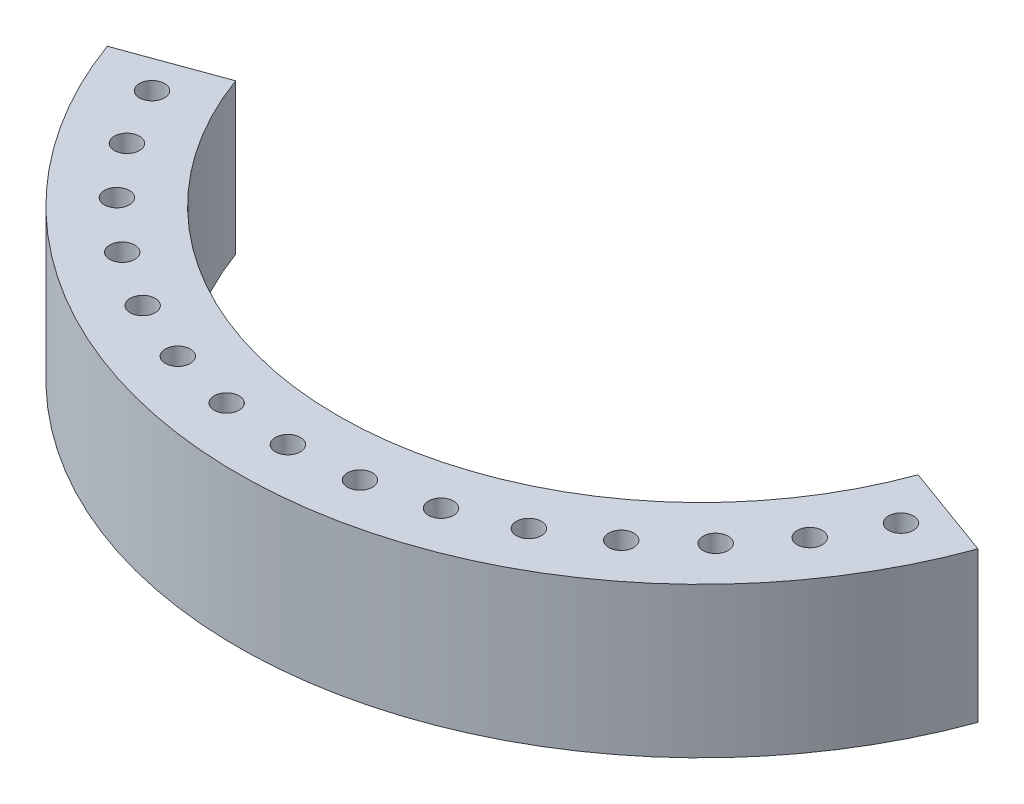
SolidWorks part; units mm, degrees
ref_plane "Front" through (0, 0, 0) normal (0, 0, 1) x (1, 0, 0)
ref_plane "Top" through (0, 0, 0) normal (0, 1, 0) x (1, 0, 0)
ref_plane "Right" through (0, 0, 0) normal (1, 0, 0) x (0, 0, -1)
sketch "Sketch1" plane through (0, 0, 0) normal (0, 1, 0) x (1, 0, 0)
  line L0 (-110.3904, -40.1788) -> (-86.5222, -31.4915)
  line L1 (86.5222, -31.4915) -> (110.3904, -40.1788)
  line L2 (-86.5222, -31.4915) -> (0, 0) construction
  line L3 (0, 0) -> (86.5222, -31.4915) construction
  line L4 (0, 0) -> (0, -117.475) construction
  line L5 (-86.5222, -31.4915) -> (0, -117.475) construction
  line L6 (0, -117.475) -> (86.5222, -31.4915) construction
  arc A0 (-110.3904, -40.1788) -> (110.3904, -40.1788) centre (0, 0) ccw
  arc A1 (-86.5222, -31.4915) -> (86.5222, -31.4915) centre (0, 0) ccw
  dimension "D1" = 25.4
  dimension "D2" = 117.475
  dimension "D3" = 140
extrude "Boss-Extrude1" add sketch "Sketch1" against normal blind 38.1
sketch "Sketch2" plane through (0, 0, 0) normal (0, 1, 0) x (1, 0, 0)
  line L0 (0, -104.775) -> (0, 0) construction
  arc A0 (-110.3904, -40.1788) -> (110.3904, -40.1788) centre (0, 0) ccw construction
  point P0 (0, -104.775)
  point P1 (0, -117.475)
  dimension "D1" = 12.7
hole_wizard "1/4 (0.2500) Dowel Hole1" positions "Sketch4" profile "Sketch3" hole size "1/4" standard "ANSI Inch" end condition up to next
sketch "Sketch4" plane through (0, 0, 0) normal (0, 1, 0) x (1, 0, 0)
  point P0 (0, -104.775)
sketch "Sketch3" plane through (0, 0, 104.775) normal (1, 0, 0) x (0, 0, 1)
  line L0 (0, 0) -> (0, 38.101)
  line L1 (0, 38.101) -> (3.175, 38.101)
  line L2 (3.175, 38.101) -> (3.175, 0)
  line L5 (3.175, 0) -> (0, 0)
  line L11 (0, -6.35) -> (0, 107.95) construction
  dimension "Thru Hole Dia." = 6.35
  dimension "Thru Hole Depth" = 38.101
pattern_circular "CirPattern1" count 8 over 65 about axis through (0, 0, 0) along (0, 1, 0) of "1/4 (0.2500) Dowel Hole1"
mirror "Mirror1" about plane through (0, 0, 0) normal (1, 0, 0) of "CirPattern1"
